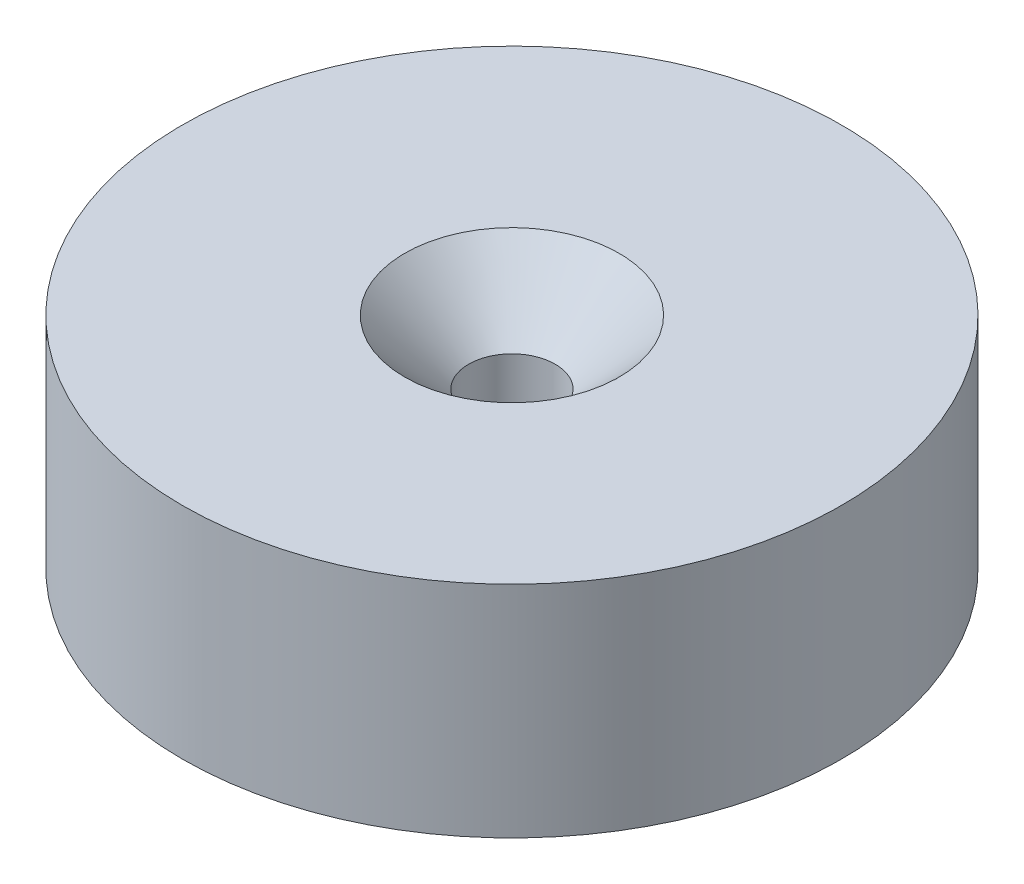
SolidWorks part; units mm, degrees
material "6061 Alloy"
ref_plane "Front Plane" through (0, 0, 0) normal (0, 0, 1) x (1, 0, 0)
ref_plane "Top Plane" through (0, 0, 0) normal (0, 1, 0) x (1, 0, 0)
ref_plane "Right Plane" through (0, 0, 0) normal (1, 0, 0) x (0, 0, -1)
sketch "Sketch1" plane through (0, 0, 0) normal (0, 1, 0) x (1, 0, 0)
  circle A0 centre (0, 0) radius 19.05
  dimension "D1" = 38.1
extrude "Boss-Extrude1" add sketch "Sketch1" along normal blind 12.7 contours A0
sketch "Sketch4" plane through (0, 12.7, 0) normal (0, 1, 0) x (1, 0, 0)
  circle A0 centre (0, 0) radius 3.175
  point P0 (0, 0)
  dimension "D1" = 6.35
hole_wizard "M6x1.0 Tapped Hole1" positions "Sketch4" profile "Sketch5" tap size "M6x1.0" standard "ANSI Metric" end condition through all
sketch "Sketch5" plane through (0, 12.7, 0) normal (1, 0, 0) x (0, 0, 1)
  line L0 (0, 0) -> (0, 12.7)
  line L1 (0, 12.7) -> (2.5, 12.7)
  line L2 (2.5, 12.7) -> (2.5, 3.7)
  line L3 (2.5, 3.7) -> (6.2, 0)
  line L5 (6.2, 0) -> (0, 0)
  line L6 (-2.5, 3.7) -> (-6.2, 0) construction
  line L11 (0, -6.35) -> (0, 107.95) construction
  dimension "Thru Tap Drill Dia." = 5
  dimension "Thru Tap Drill Depth" = 12.7
  dimension "Near C'Sink Dia." = 12.4
  dimension "Near C'Sink Angle" = 90
cosmetic thread "Hole Thread1" parameters "D2"=6
equation "\"liddiameter\"= 1.5in"
equation "\"lidheight\"= 0.5in"
equation "\"lidscrewholediff\"= 0.5in"
equation "\"D1@Sketch1\"=\"liddiameter\""
equation "\"D1@Boss-Extrude1\"=\"lidheight\""
